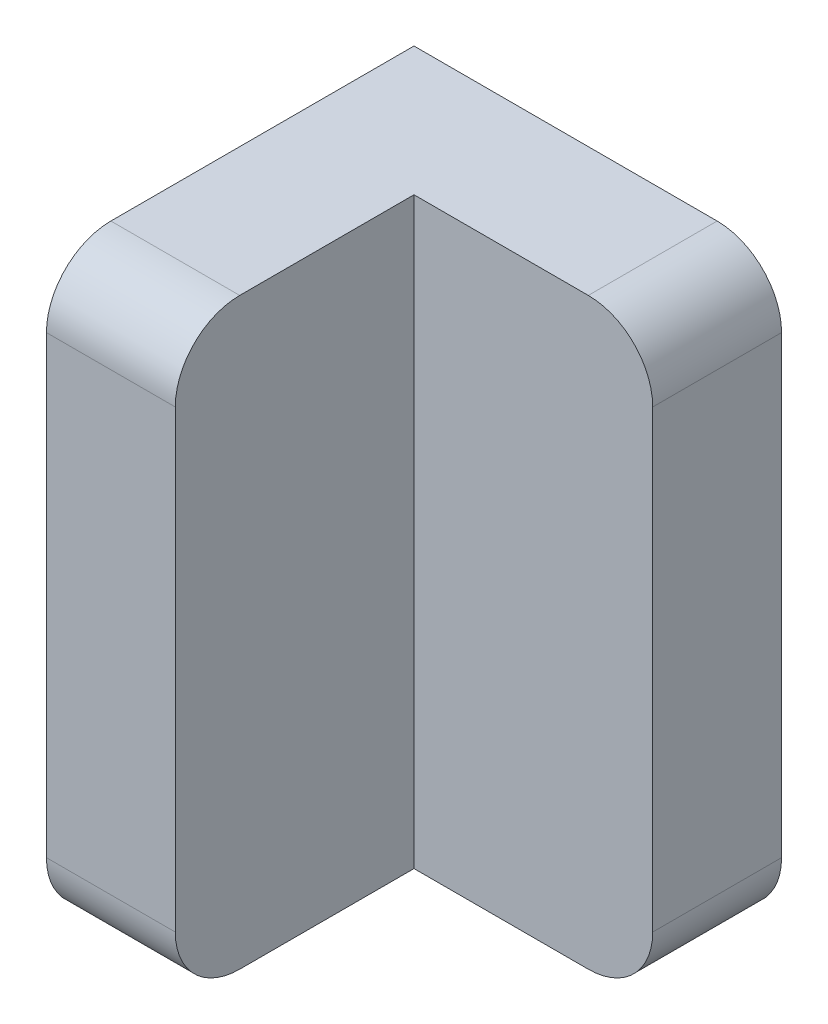
SolidWorks part; units mm, degrees
ref_plane "前视基准面" through (0, 0, 0) normal (0, 0, 1) x (1, 0, 0)
ref_plane "上视基准面" through (0, 0, 0) normal (0, 1, 0) x (1, 0, 0)
ref_plane "右视基准面" through (0, 0, 0) normal (1, 0, 0) x (0, 0, -1)
other "Configuration Table"
sketch "草图1" plane through (0, 0, 0) normal (0, 0, 1) x (1, 0, 0)
  line L0 (0, -3.85) -> (4, -3.85)
  line L1 (4.85, -3) -> (4.85, 3)
  line L2 (4, 3.85) -> (0, 3.85)
  line L3 (0, 3.85) -> (0, -3.85)
  arc A0 (4, -3.85) -> (4.85, -3) centre (4, -3) ccw
  arc A1 (4.85, 3) -> (4, 3.85) centre (4, 3) ccw
extrude "Flush_roof_lens_T1.7_clearance0.15" add sketch "草图1" along normal blind 1.7
sketch "草图2" plane through (0, 0, 0) normal (1, 0, 0) x (0, 0, -1)
  line L0 (0, -3.85) -> (0, 3.85)
  line L1 (0, 3.85) -> (-4, 3.85)
  line L2 (-4.85, 3) -> (-4.85, -3)
  line L3 (-4, -3.85) -> (0, -3.85)
  arc A0 (-4, 3.85) -> (-4.85, 3) centre (-4, 3) ccw
  arc A1 (-4.85, -3) -> (-4, -3.85) centre (-4, -3) ccw
extrude "Flush_side_lens_T1.7_clearance0.15" add sketch "草图2" along normal blind 1.7
